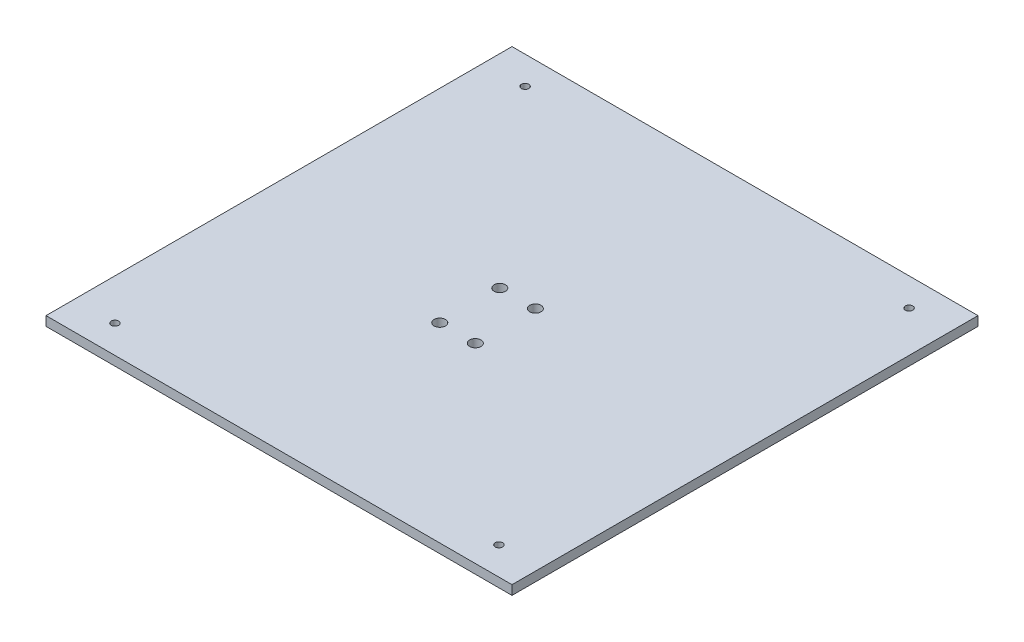
SolidWorks part; units mm, degrees
ref_plane "Front Plane" through (0, 0, 0) normal (0, 0, 1) x (1, 0, 0)
ref_plane "Top Plane" through (0, 0, 0) normal (0, 1, 0) x (1, 0, 0)
ref_plane "Right Plane" through (0, 0, 0) normal (1, 0, 0) x (0, 0, -1)
sketch "Sketch2" plane through (0, 0, 0) normal (0, 1, 0) x (1, 0, 0)
  line L1 (0, 0) -> (250, 0)
  line L2 (0, 0) -> (0, 250)
  line L3 (0, 250) -> (250, 250)
  line L4 (250, 0) -> (250, 250)
  dimension "D1" = 250
  dimension "D2" = 250
extrude "Boss-Extrude1" add sketch "Sketch2" along normal blind 5
sketch "Sketch3" plane through (0, 5, 0) normal (0, 1, 0) x (1, 0, 0)
  circle A0 centre (22, 15) radius 2
  circle A1 centre (108.9, 134.54) radius 3.05
  circle A2 centre (127.98, 134.54) radius 3.05
  circle A3 centre (127.98, 102.34) radius 3.05
  circle A4 centre (108.9, 102.34) radius 3.05
  dimension "D1" = 2
  dimension "D2" = 2
extrude "Cut-Extrude1" cut sketch "Sketch3" against normal through all
pattern_linear "LPattern1" count 2 spacing 220 along (0, 0, -1) count 2 spacing 206 along (1, 0, 0) of "Cut-Extrude1"
